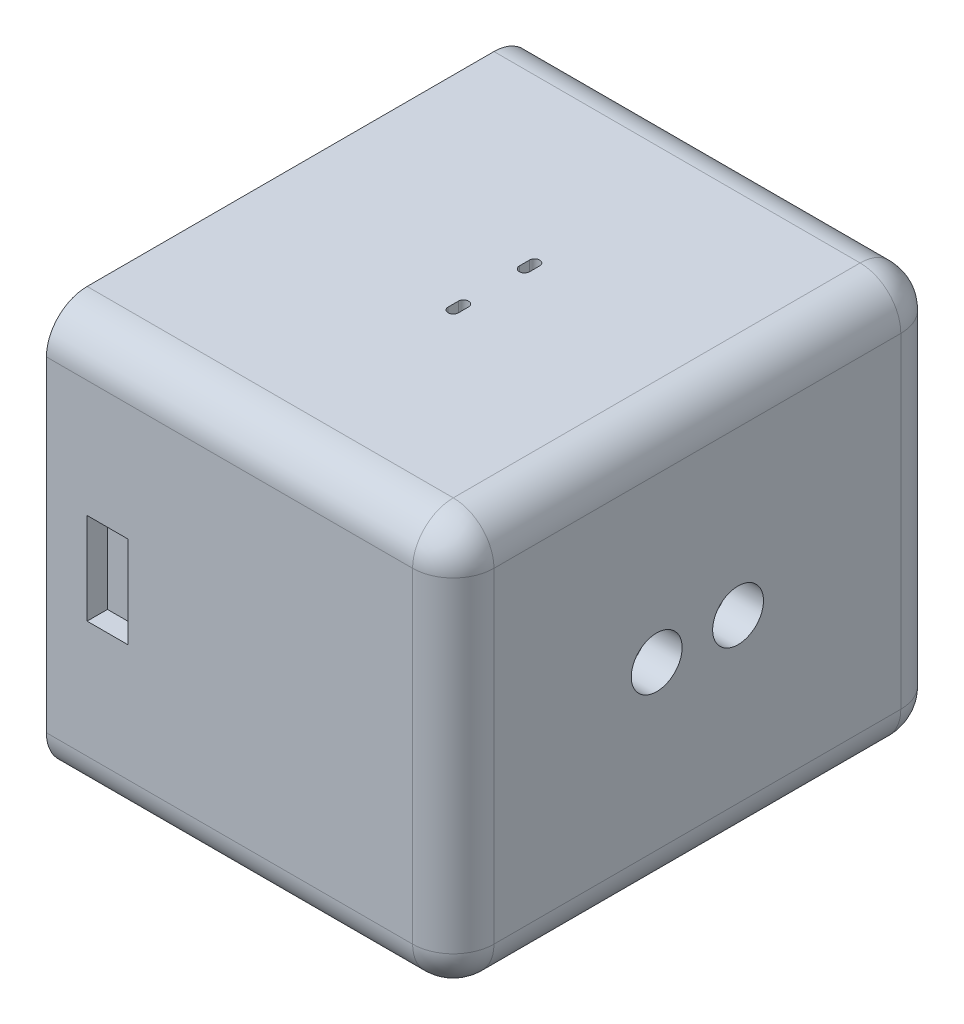
SolidWorks part; units mm, degrees
ref_plane "Front Plane" through (0, 0, 0) normal (0, 0, 1) x (1, 0, 0)
ref_plane "Top Plane" through (0, 0, 0) normal (0, 1, 0) x (1, 0, 0)
ref_plane "Right Plane" through (0, 0, 0) normal (1, 0, 0) x (0, 0, -1)
sketch "Sketch1" plane through (0, 0, 0) normal (0, 1, 0) x (1, 0, 0)
  line L0 (0, 0) -> (127, 0)
  line L1 (127, 0) -> (127, 152.4)
  line L2 (127, 152.4) -> (0, 152.4)
  line L3 (0, 152.4) -> (0, 0)
  dimension "D1" = 152.4
  dimension "D2" = 127
extrude "Boss-Extrude1" add sketch "Sketch1" along normal blind 127
shell "Shell1" thickness 12.7
fillet "Fillet1" radius 12.7 8 edges at (63.5, 0, -152.4) (127, 63.5, -152.4) (127, 0, -76.2) (63.5, 0, 0) (127, 63.5, 0) (127, 127, -76.2) (63.5, 127, 0) (63.5, 127, -152.4)
sketch "Sketch3" plane through (0, 0, 0) normal (0, -1, 0) x (1, 0, 0)
  line L0 (0, -139.7) -> (0, -12.7) construction
  line L1 (25.4, -41.275) -> (49.3889, -41.275)
  line L2 (25.4, -41.275) -> (25.4, -111.125)
  line L3 (25.4, -111.125) -> (49.3889, -111.125)
  line L4 (49.3889, -41.275) -> (49.3889, -111.125)
  point P6 (0, -76.2)
  point P7 (25.4, -76.2)
  dimension "D1" = 25.4
  dimension "D2" = 69.85
  dimension "D3" = 23.9889
extrude "Cut-Extrude1" cut sketch "Sketch3" against normal blind 9.525
sketch "Sketch4" plane through (0, 12.7, 0) normal (0, 1, 0) x (1, 0, 0)
  line L0 (0, 139.7) -> (0, 12.7) construction
  line L1 (19.9314, 115.8875) -> (54.8564, 115.8875)
  line L2 (19.9314, 115.8875) -> (19.9314, 36.5125)
  line L3 (19.9314, 36.5125) -> (54.8564, 36.5125)
  line L4 (54.8564, 115.8875) -> (54.8564, 36.5125)
  point P6 (0, 76.2)
  point P7 (19.9314, 76.2)
  dimension "D1" = 19.9314
  dimension "D2" = 34.925
  dimension "D3" = 79.375
extrude "Cut-Extrude2" cut sketch "Sketch4" against normal up to vertex (3.175 mm away) contours L2 L3 L4 L1 up to point (49.3889, 9.525, -41.275)
sketch "Sketch5" plane through (0, 0, 0) normal (0, 0, 1) x (1, 0, 0)
  line L1 (12.7, 49.2125) -> (25.4, 49.2125)
  line L2 (12.7, 49.2125) -> (12.7, 77.7875)
  line L3 (12.7, 77.7875) -> (25.4, 77.7875)
  line L4 (25.4, 49.2125) -> (25.4, 77.7875)
  line L5 (0, 114.3) -> (0, 12.7) construction
  point P4 (0, 63.5)
  point P7 (12.7, 63.5)
  dimension "D1" = 12.7
  dimension "D2" = 12.7
  dimension "D3" = 28.575
extrude "Cut-Extrude3" cut sketch "Sketch5" against normal blind 6.35
sketch "Sketch6" plane through (0, 0, -6.35) normal (0, 0, 1) x (1, 0, 0)
  line L1 (15.875, 77.7875) -> (22.225, 77.7875)
  line L2 (15.875, 77.7875) -> (15.875, 73.9775)
  line L3 (15.875, 73.9775) -> (22.225, 73.9775)
  line L4 (22.225, 77.7875) -> (22.225, 73.9775)
  line L5 (25.4, 77.7875) -> (12.7, 77.7875) construction
  point P4 (19.05, 77.7875)
  point P9 (19.05, 77.7875)
  dimension "D1" = 6.35
  dimension "D2" = 3.81
  dimension "D3" = 0
extrude "Cut-Extrude4" cut sketch "Sketch6" against normal up to next
sketch "Sketch7" plane through (127, 0, 0) normal (1, 0, 0) x (0, 0, -1)
  line L0 (55.5625, 63.5) -> (96.8375, 63.5) construction
  line L1 (139.7, 114.3) -> (12.7, 114.3) construction
  line L2 (139.7, 12.7) -> (139.7, 114.3) construction
  circle A0 centre (63.5, 63.5) radius 7.9375
  circle A1 centre (88.9, 63.5) radius 7.9375
  point P2 (76.2, 63.5)
  point P5 (76.2, 114.3)
  point P8 (139.7, 63.5)
  dimension "D2" = 15.875
  dimension "D3" = 15.875
  dimension "D1" = 41.275
extrude "Cut-Extrude5" cut sketch "Sketch7" against normal blind 11.1125
ref_plane "Plane1" through (115.8875, 0, 0) normal (1, 0, 0) x (0, 0, -1)
sketch "Sketch8" plane through (115.8875, 0, 0) normal (1, 0, 0) x (0, 0, -1)
  line L0 (12.7, 114.3) -> (12.7, 12.7) construction
  line L1 (53.1813, 73.8188) -> (99.2188, 73.8188)
  line L2 (53.1813, 73.8188) -> (53.1813, 53.1812)
  line L3 (53.1813, 53.1812) -> (99.2188, 53.1813)
  line L4 (99.2188, 73.8188) -> (99.2188, 53.1813)
  line L5 (139.7, 114.3) -> (12.7, 114.3) construction
  point P4 (53.1813, 63.5)
  point P7 (12.7, 63.5)
  point P8 (76.2, 73.8187)
  point P11 (76.2, 114.3)
  dimension "D1" = 20.6375
  dimension "D2" = 46.0375
extrude "Cut-Extrude6" cut sketch "Sketch8" against normal up to next
sketch "Sketch9" plane through (0, 0, -152.4) normal (0, 0, -1) x (-1, 0, 0)
  line L0 (0, 114.3) -> (0, 12.7) construction
  circle A0 centre (-38.1, 76.2) radius 2.3812
  circle A1 centre (-38.1, 63.5) radius 2.3812
  circle A2 centre (-38.1, 50.8) radius 2.3812
  point P9 (0, 63.5)
  dimension "D1" = 4.7625
  dimension "D2" = 4.7625
  dimension "D3" = 4.7625
  dimension "D4" = 12.7
  dimension "D5" = 12.7
  dimension "D6" = 38.1
extrude "Cut-Extrude7" cut sketch "Sketch9" against normal up to next
sketch "Sketch10" plane through (0, 127, 0) normal (0, 1, 0) x (1, 0, 0)
  line L0 (61.9125, 88.9) -> (61.9125, 85.725)
  line L1 (65.0875, 85.725) -> (65.0875, 88.9)
  line L4 (61.9125, 66.675) -> (61.9125, 63.5)
  line L5 (65.0875, 63.5) -> (65.0875, 66.675)
  line L6 (114.3, 12.7) -> (114.3, 139.7) construction
  line L7 (114.3, 139.7) -> (0, 139.7) construction
  arc A0 (61.9125, 85.725) -> (65.0875, 85.725) centre (63.5, 85.725) ccw
  arc A1 (65.0875, 88.9) -> (61.9125, 88.9) centre (63.5, 88.9) ccw
  arc A4 (61.9125, 63.5) -> (65.0875, 63.5) centre (63.5, 63.5) ccw
  arc A5 (65.0875, 66.675) -> (61.9125, 66.675) centre (63.5, 66.675) ccw
  dimension "D1" = 3.175
  dimension "D2" = 1.5875
  dimension "D3" = 3.175
  dimension "D4" = 25.4
  dimension "D5" = 50.8
  dimension "D6" = 50.8
  dimension "D7" = 50.8
  dimension "D8" = 1.5875
extrude "Cut-Extrude8" cut sketch "Sketch10" against normal up to next
